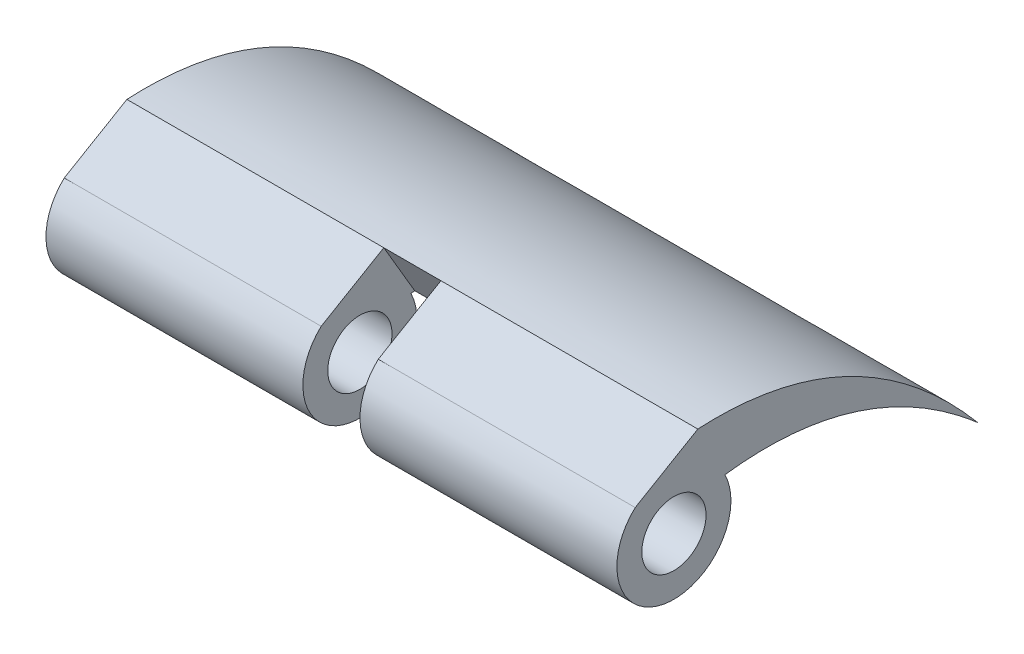
SolidWorks part; units mm, degrees
ref_plane "Front Plane" through (0, 0, 0) normal (0, 0, 1) x (1, 0, 0)
ref_plane "Top Plane" through (0, 0, 0) normal (0, 1, 0) x (1, 0, 0)
ref_plane "Right Plane" through (0, 0, 0) normal (1, 0, 0) x (0, 0, -1)
sketch "Sketch1" plane through (0, 0, 0) normal (1, 0, 0) x (0, 0, -1)
  line L0 (-1.0845, 1.1734) -> (0.67, 2.2019)
  circle A0 centre (0, 0) radius 0.9
  arc A2 (-1.0845, 1.1734) -> (1.4299, 0.713) centre (0, 0) ccw
  spline S0 degree 2 poles (0.67, 2.2019) (5.142, 2.4416) (8.5217, -1.5705) knots 0 0 0 1 1 1
  spline S1 degree 2 poles (1.4299, 0.713) (5.3288, 1.2117) (8.5217, -1.5705) knots 0 0 0 1 1 1
  point P3 (1.4094, 0.7029)
  point P6 (-1.0845, 1.1734)
  point P9 (0.67, 2.1549)
  dimension "D1" = 1.8
extrude "Boss-Extrude1" add sketch "Sketch1" along normal blind 16
sketch "Sketch2" plane through (0, 1.3464, 0.7893) normal (0, 0.8627, 0.5057) x (1, 0, 0)
  line L0 (16, 1.6916) -> (0, 1.6916) construction
  line L1 (7.2, 1.6916) -> (8.8, 1.6916)
  line L2 (7.2, 1.6916) -> (7.2, -2.5091)
  line L3 (7.2, -2.5091) -> (8.8, -2.5091)
  line L4 (8.8, 1.6916) -> (8.8, -2.5091)
  line L5 (0, 1.6916) -> (0, -0.3422) construction
  line L6 (16, 1.6916) -> (16, -0.3422) construction
  dimension "D1" = 7.2
  dimension "D2" = 7.2
extrude "Cut-Extrude1" cut sketch "Sketch2" against normal blind 10
